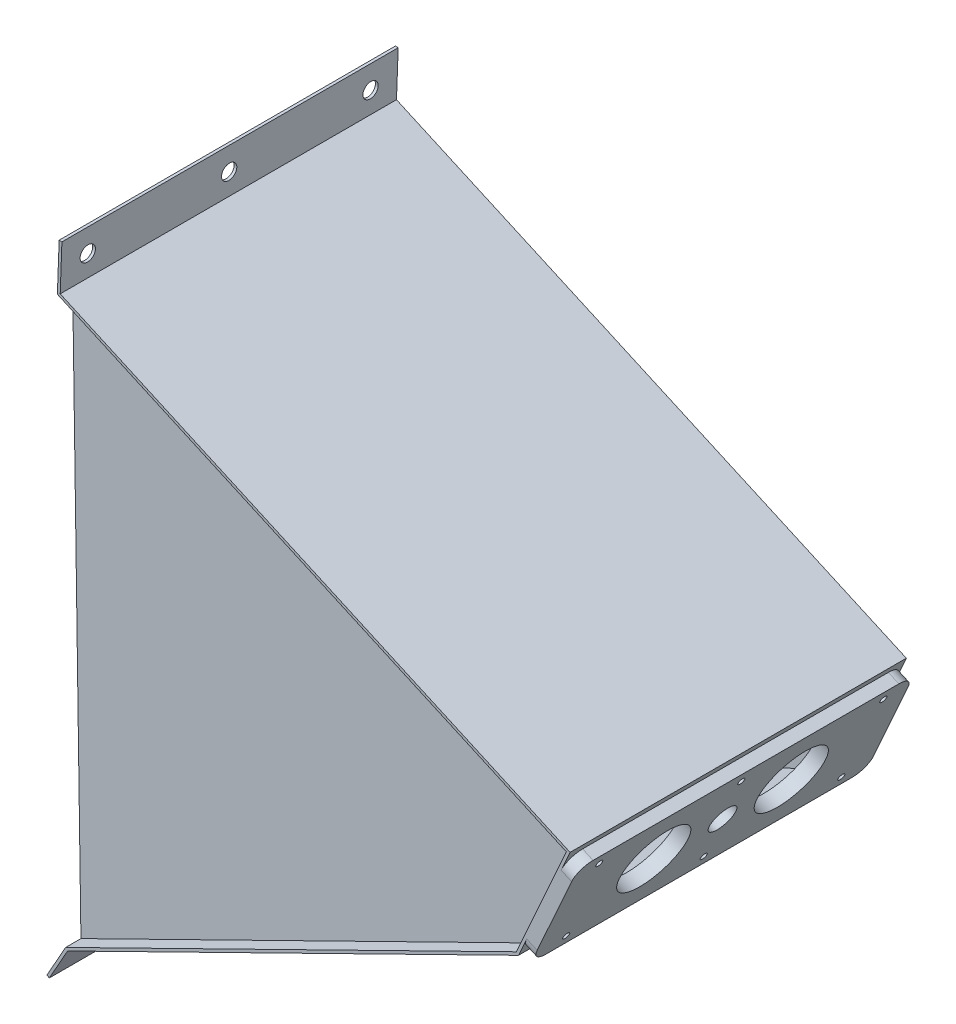
SolidWorks part; units mm, degrees
ref_plane "Plane Left" through (0, 0, 0) normal (0, 0, 1) x (1, 0, 0)
ref_plane "Plane Top" through (0, 0, 0) normal (0, 1, 0) x (1, 0, 0)
ref_plane "Plane Front" through (0, 0, 0) normal (1, 0, 0) x (0, 0, -1)
sketch "Sketch, Layout in Left plane" plane through (0, 0, 0) normal (0, 0, 1) x (1, 0, 0)
  line L0 (0, 0) -> (2438.4, 0) construction
  line L1 (2438.4, 0) -> (3438.525, 5791.2) construction
  line L2 (2438.4, 0) -> (3591.5584, 144.7101) construction
  line L4 (9.525, -304.8) -> (3438.525, 5791.2)
  line L5 (2438.4, 0) -> (2119.6797, -1845.5425) construction
  line L6 (2438.4, 0) -> (1532.9859, -517.7594) construction
  line L7 (1532.9859, -517.7594) -> (3591.5584, 144.7101) construction
  line L8 (1532.9859, -517.7594) -> (2119.6797, -1845.5425) construction
  line L9 (1532.9859, -517.7594) -> (3210.1749, -1270.1567) construction
  line L10 (2438.4, 0) -> (3428.7883, 566.3517) construction
  line L11 (1724.025, 2743.2) -> (1159.8354, 3060.5567)
  line L12 (1724.025, 2743.2) -> (2438.4, 0) construction
  line L13 (2438.4, 0) -> (9.525, -304.8) construction
  line L14 (3210.1749, -1270.1567) -> (2438.4, 0) construction
  line L15 (1985.693, -258.8797) -> (2769.1787, -1628.9737) construction
  line L16 (2119.6797, -1845.5425) -> (3591.5584, 144.7101)
  line L17 (1724.025, 2743.2) -> (771.525, 2743.2) construction
  line L18 (1985.693, -258.8797) -> (2830.8492, -883.9096) construction
  line L19 (2818.8646, -1810.0806) -> (3303.3993, -1154.9) construction
  line L20 (2855.619, -850.4162) -> (3241.0348, -1135.448)
  line L21 (1532.9859, -517.7594) -> (2.9158, 168.6396) construction
  line L24 (1532.9859, -517.7594) -> (542.5977, -1084.111) construction
  line L25 (9.5556, -304.7457) -> (384.0395, -120.6496)
  line L26 (384.0395, -120.6496) -> (425.6251, -27.9501)
  line L27 (425.6251, -27.9501) -> (2.6835, 161.7841)
  line L30 (2.6835, 161.7841) -> (4.161, 201.4568)
  line L31 (588.3016, -156.6053) -> (269.3395, -13.517) construction
  line L33 (396.9265, -122.951) -> (435.913, -36.0452)
  line L34 (246.0198, 52.6219) -> (162.8486, -132.7771)
  line L35 (162.8486, -132.7771) -> (180.2298, -140.5744)
  line L36 (180.2298, -140.5744) -> (263.4009, 44.8247)
  line L37 (9.5556, -304.7457) -> (-6.0102, -332.4182)
  line L38 (396.9265, -122.951) -> (385.339, -117.7528)
  ellipse E1 centre (1985.693, -258.8797) end of major axis (542.5977, -1084.111) minor radius 1578.2926 (542.5977, -1084.111) -> (3428.7883, 566.3517) ccw
  parabola Q1 (24.219, -486.0276) -> (3732.0885, 6033.3488) focus (2438.4, 0) apex (0, 0)
  point P4 (416.4197, -79.4981)
  point P13 (453.548, -33.5168)
  point P45 (404.8323, -74.2999)
  dimension "D1" = 2438.4
  dimension "D2" = 254
  dimension "D3" = 304.8
  dimension "D4" = 99.798
  dimension "D5" = 6096
  dimension "D6" = 42
  dimension "D7" = 42
  dimension "D8" = 29.763
  dimension "D9" = 53.924
  dimension "D10" = 95.25
  dimension "D11" = 2475.3853
  dimension "D12" = 50.8
  dimension "D13" = 463.55
  dimension "D14" = 50.8
  dimension "D15" = 31.75
  dimension "D16" = 57.15
  dimension "D17" = 12.7
  dimension "D18" = 19.05
  dimension "D19" = 190.5
  dimension "D20" = 203.2
  dimension "D21" = 39.7002
  dimension "2c" = 1043.0002
  dimension "D22" = 0.0623
  dimension "D23" = 39.66
  dimension "magrad" = 1662.3871
  dimension "D24" = 417.2883
ref_plane "Pl-4 Primary face plane" through (1724.025, 2743.2, 0) normal (-0.8716, 0.4903, 0) x (0, 0, 1)
sketch "Sketch9" plane through (0, 0, 0) normal (0, 0, 1) x (1, 0, 0)
  line L10 (2.6835, 161.7841) -> (4.161, 201.4568)
  line L11 (9.5556, -304.7457) -> (-6.0102, -332.4182)
  line L12 (9.5556, -304.7457) -> (384.0395, -120.6496)
  line L13 (384.0395, -120.6496) -> (425.6251, -27.9501)
  line L14 (425.6251, -27.9501) -> (2.6835, 161.7841)
extrude "Extrude-Thin1 0.090" add sketch "Sketch9" along normal mid plane 279.4 thin
sketch "Sketch13" plane through (366.8429, -164.568, 0) normal (0.9124, -0.4093, 0) x (0, 0, -1)
  line L1 (-127, 145.5347) -> (127, 145.5347)
  line L2 (-139.7, 132.8347) -> (-139.7, 62.9847)
  line L3 (-127, 50.2847) -> (127, 50.2847)
  line L4 (139.7, 132.8347) -> (139.7, 62.9847)
  arc A0 (127, 50.2847) -> (139.7, 62.9847) centre (127, 62.9847) ccw
  arc A1 (-139.7, 62.9847) -> (-127, 50.2847) centre (-127, 62.9847) ccw
  arc A2 (-127, 145.5347) -> (-139.7, 132.8347) centre (-127, 132.8347) ccw
  arc A3 (127, 145.5347) -> (139.7, 132.8347) centre (127, 132.8347) cw
  point P12 (0, 50.2847)
  point P13 (139.7, 97.9097)
  dimension "D1" = 12.7
  dimension "D2" = 95.25
  dimension "D3" = 279.4
extrude "BE-00 Front Bearing Plate" add sketch "Sketch13" along normal blind 9.525
sketch "Sketch10" plane through (-463.2629, -2038.2499, 0) normal (-0.9124, 0.4093, 0) x (0, 0, -1)
  line L0 (0, -2049.3093) -> (0, -29.7086) construction
  circle A0 centre (-118.013, -2185.319) radius 2.7813
  circle A1 centre (0, -2147.219) radius 11.1125
  circle A2 centre (57.15, -2147.219) radius 28.575
  circle A3 centre (114.3, -2109.119) radius 2.7813
  circle A4 centre (118.013, -2185.319) radius 2.7813
  circle A5 centre (0, -2109.119) radius 2.7813
  circle A6 centre (0, -2185.319) radius 2.7813
  circle A7 centre (-114.3, -2109.119) radius 2.7813
  circle A8 centre (-57.15, -2147.219) radius 28.575
  dimension "D3" = 57.15
  dimension "D4" = 22.225
  dimension "D7" = 5.5626
  dimension "D2" = 57.15
  dimension "D5" = 38.1
  dimension "D6" = 38.1
  dimension "D8" = 114.3
extrude "CE-00 Front Holes" cut sketch "Sketch10" along normal blind 25.4
sketch "Sketch11" plane through (-26.305, -678.029, 0) normal (-0.9993, 0.0372, 0) x (0, 0, -1)
  circle A0 centre (-117.475, -860.1859) radius 6.35
  circle A1 centre (0, -860.1859) radius 6.35
  circle A2 centre (117.475, -860.1859) radius 6.35
  dimension "D2" = 12.7
  dimension "D3" = 117.475
  dimension "D4" = 117.475
extrude "CE-00 Uppoer Holes" cut sketch "Sketch11" along normal blind 25.4
sketch "Sketch12" plane through (139.469, -78.4513, 0) normal (0.8716, -0.4903, 0) x (0, 0, -1)
  line L1 (-19.05, -253.3665) -> (19.05, -253.3665)
  line L2 (-25.4, -259.7165) -> (-25.4, -304.5137)
  line L3 (-25.4, -304.5137) -> (25.4, -304.5137)
  line L4 (25.4, -259.7165) -> (25.4, -304.5137)
  circle A0 centre (101.6, -280.0365) radius 6.5532
  circle A1 centre (50.8, -280.0365) radius 6.5532
  circle A2 centre (0, -280.0365) radius 7.9375 construction
  circle A3 centre (-50.8, -280.0365) radius 6.5532
  circle A4 centre (-101.6, -280.0365) radius 6.5532
  arc A5 (-19.05, -253.3665) -> (-25.4, -259.7165) centre (-19.05, -259.7165) ccw
  arc A6 (19.05, -253.3665) -> (25.4, -259.7165) centre (19.05, -259.7165) cw
  point P20 (0, -304.5137)
  dimension "D6" = 13.1064
  dimension "D7" = 15.875
  dimension "D8" = 6.35
  dimension "D1" = 19.05
  dimension "D2" = 50.8
  dimension "D3" = 50.8
  dimension "D4" = 50.8
  dimension "D5" = 50.8
  dimension "D9" = 50.8
  dimension "D10" = 7.62
extrude "CE-00 Lower Holes" cut sketch "Sketch12" against normal mid plane 25.4
sketch "Sketch14" plane through (0, 0, 0) normal (0, 0, 1) x (1, 0, 0)
  line L0 (2.6835, 161.7841) -> (425.6251, -27.9501)
  line L1 (425.6251, -27.9501) -> (384.0395, -120.6496)
  line L2 (384.0395, -120.6496) -> (9.5556, -304.7457)
  line L3 (9.5556, -304.7457) -> (2.6835, 161.7841)
extrude "BE-00 Side Panel" add sketch "Sketch14" along normal blind 3.175 from offset 127 offset against normal yes
mirror "MI-00 Side Panel" about plane through (0, 0, 0) normal (0, 0, 1) of "BE-00 Side Panel"
